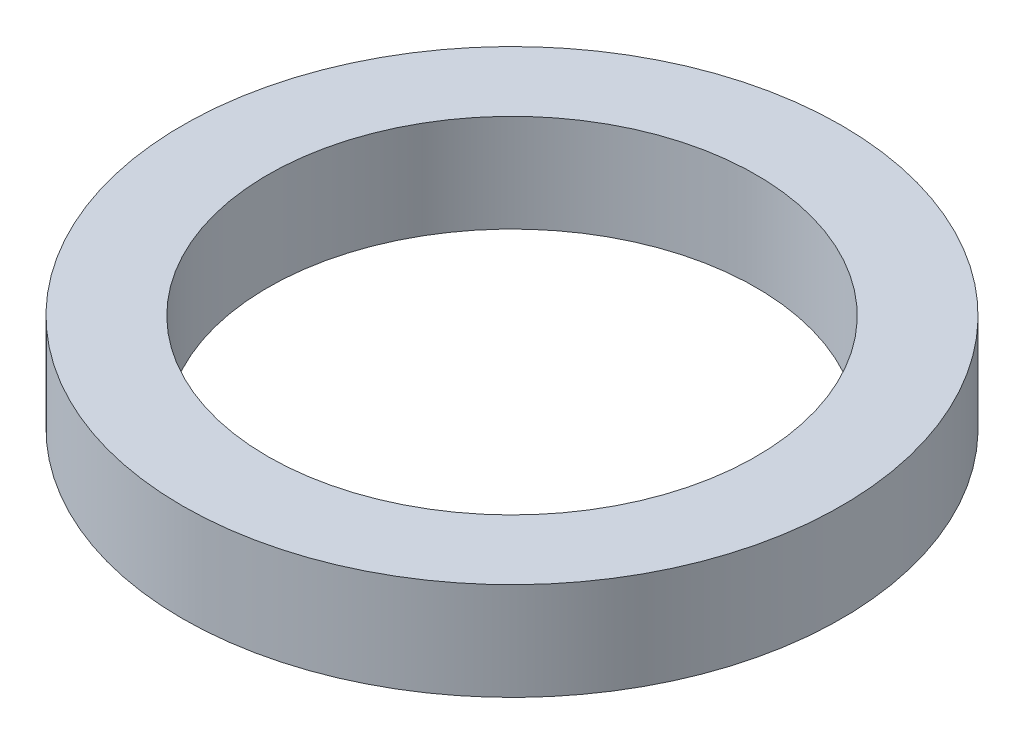
SolidWorks part; units mm, degrees
ref_plane "前视基准面" through (0, 0, 0) normal (0, 0, 1) x (1, 0, 0)
ref_plane "上视基准面" through (0, 0, 0) normal (0, 1, 0) x (1, 0, 0)
ref_plane "右视基准面" through (0, 0, 0) normal (1, 0, 0) x (0, 0, -1)
sketch "草图1" plane through (0, 0, 0) normal (0, 1, 0) x (1, 0, 0)
  circle A0 centre (0, 0) radius 13.5
  circle A1 centre (0, 0) radius 10
  dimension "D1" = 27
  dimension "D2" = 20
extrude "凸台-拉伸1" add sketch "草图1" along normal blind 4
